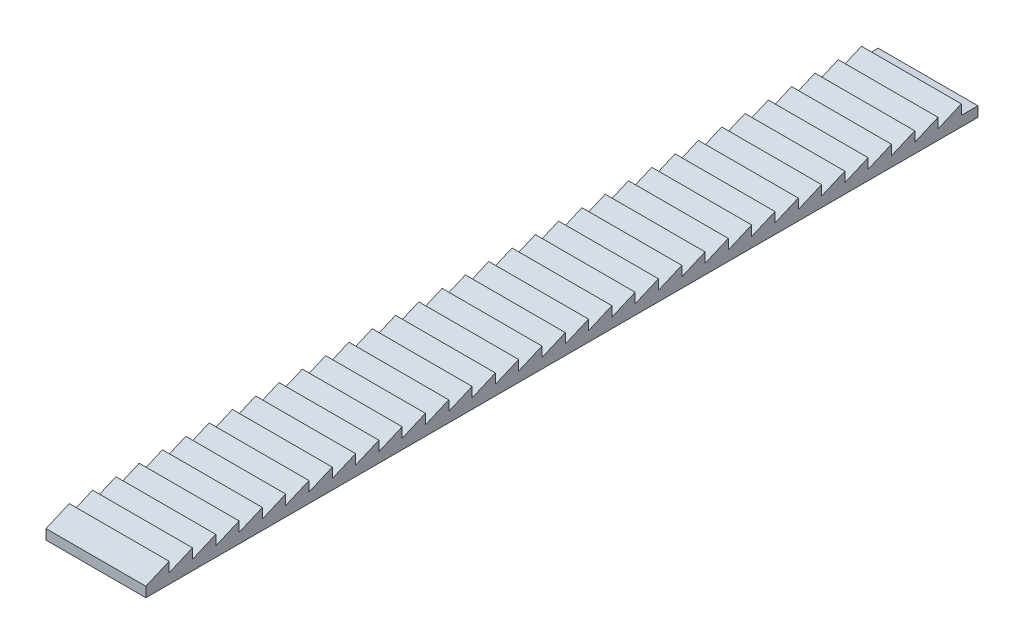
SolidWorks part; units mm, degrees
ref_plane "정면" through (0, 0, 0) normal (0, 0, 1) x (1, 0, 0)
ref_plane "윗면" through (0, 0, 0) normal (0, 1, 0) x (1, 0, 0)
ref_plane "우측면" through (0, 0, 0) normal (1, 0, 0) x (0, 0, -1)
sketch "스케치1" plane through (0, 0, 0) normal (0, 1, 0) x (1, 0, 0)
  line L1 (-15, -125) -> (15, -125)
  line L2 (-15, -125) -> (-15, 125)
  line L3 (-15, 125) -> (15, 125)
  line L4 (15, -125) -> (15, 125)
  line L5 (-15, -125) -> (15, 125) construction
  line L6 (-15, 125) -> (15, -125) construction
  point P0 (0, 0)
  dimension "D1" = 30
  dimension "D2" = 250
extrude "보스-돌출1" add sketch "스케치1" along normal blind 3
sketch "스케치3" plane through (0, 0, 0) normal (1, 0, 0) x (0, 0, -1)
  line L0 (-125, 3) -> (-118, 6)
  line L1 (-118, 6) -> (-118, 3)
  line L2 (-125, 3) -> (125, 3) construction
  line L3 (-118, 3) -> (-125, 3)
  dimension "D1" = 7
  dimension "D2" = 3
extrude "보스-돌출2" add sketch "스케치3" along normal mid plane 30 contours L3 L0 L1
pattern_linear "선형 패턴1" count 35 spacing 7 along (0, 0, -1) of "보스-돌출2"
